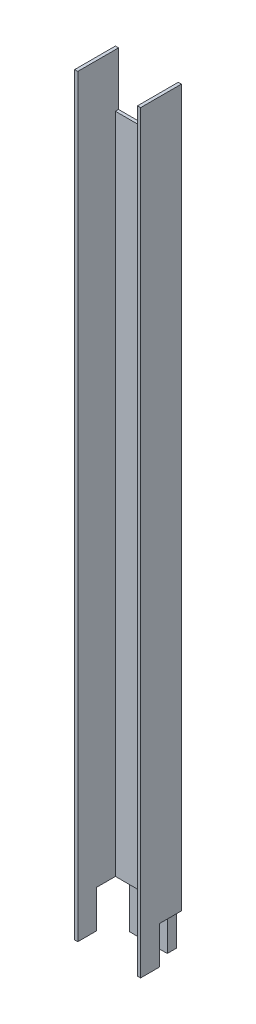
SolidWorks part; units mm, degrees
ref_plane "Front Plane" through (0, 0, 0) normal (0, 0, 1) x (1, 0, 0)
ref_plane "Top Plane" through (0, 0, 0) normal (0, 1, 0) x (1, 0, 0)
ref_plane "Right Plane" through (0, 0, 0) normal (1, 0, 0) x (0, 0, -1)
sketch "Sketch2" plane through (0, 0, 0) normal (0, 1, 0) x (1, 0, 0)
  line L0 (-10.5, -6.5) -> (-10.5, 6.5)
  line L7 (-10.5, 6.5) -> (10.5, 6.5)
  line L8 (10.5, 6.5) -> (10.5, -6.5)
  line L9 (10.5, -6.5) -> (9.5, -6.5)
  line L10 (9.5, -6.5) -> (9.5, 5.5)
  line L11 (9.5, 5.5) -> (-9.5, 5.5)
  line L12 (-9.5, 5.5) -> (-9.5, -6.5)
  line L13 (-9.5, -6.5) -> (-10.5, -6.5)
  point P0 (0, 0)
  dimension "D1" = 21
  dimension "D2" = 13
  dimension "D3" = 1
  dimension "D4" = 1
  dimension "D5" = 12
extrude "Boss-Extrude1" add sketch "Sketch2" along normal blind 240
sketch "Sketch3" plane through (0, 240, 0) normal (0, 1, 0) x (1, 0, 0)
  line L0 (-9.5, 5.5) -> (-9.5, 6.5)
  line L1 (10.5, 6.5) -> (-10.5, 6.5) construction
  line L2 (-9.5, 6.5) -> (9.5, 6.5)
  line L3 (9.5, 6.5) -> (9.5, 5.5)
  line L4 (9.5, 5.5) -> (-9.5, 5.5)
extrude "Cut-Extrude1" cut sketch "Sketch3" against normal blind 17
sketch "Sketch4" plane through (0, 0, 0) normal (0, -1, 0) x (1, 0, 0)
  line L0 (-9.5, -5.5) -> (-9.5, -6.5)
  line L1 (-9.5, -6.5) -> (9.5, -6.5)
  line L2 (9.5, -6.5) -> (9.5, -5.5)
  line L3 (9.5, -5.5) -> (-9.5, -5.5)
extrude "Cut-Extrude2" cut sketch "Sketch4" against normal blind 11
sketch "Sketch5" plane through (0, 0, -6.5) normal (0, 0, -1) x (-1, 0, 0)
  line L10 (-6, 41) -> (6, 41)
  line L11 (6, 11) -> (-6, 11)
  line L12 (-6, 41) -> (-6, 11)
  line L13 (6, 41) -> (6, 11)
  dimension "D2" = 30
extrude "Boss-Extrude2" add sketch "Sketch5" along normal blind 3
sketch "Sketch6" plane through (0, 11, 0) normal (0, -1, 0) x (1, 0, 0)
  line L0 (-6, -6.5) -> (6, -6.5)
  line L1 (6, -6.5) -> (6, -9.5)
  line L2 (6, -9.5) -> (6, -6.5) construction
  line L3 (6, -9.5) -> (-6, -9.5)
  line L4 (-6, -9.5) -> (-6, -6.5)
extrude "Boss-Extrude3" add sketch "Sketch6" along normal blind 13
sketch "Sketch7" plane through (10.5, 0, 0) normal (1, 0, 0) x (0, 0, -1)
  line L2 (6.5, 0) -> (-0.5, 0)
  line L3 (6.5, 0) -> (6.5, 12)
  line L4 (6.5, 12) -> (-0.5, 12)
  line L5 (-0.5, 0) -> (-0.5, 12)
  dimension "D1" = 7
  dimension "D2" = 12
extrude "Cut-Extrude3" cut sketch "Sketch7" against normal blind 30 contours L3 L2 L5 L4
